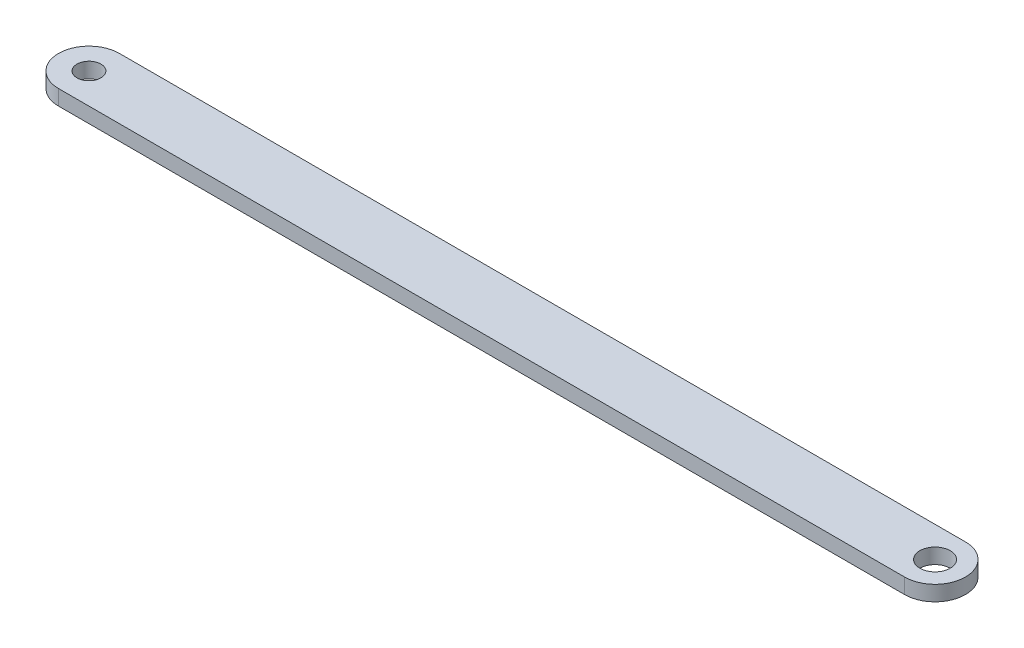
SolidWorks part; units mm, degrees
ref_plane "Front Plane" through (0, 0, 0) normal (0, 0, 1) x (1, 0, 0)
ref_plane "Top Plane" through (0, 0, 0) normal (0, 1, 0) x (1, 0, 0)
ref_plane "Right Plane" through (0, 0, 0) normal (1, 0, 0) x (0, 0, -1)
sketch "Sketch1" plane through (0, 0, 0) normal (0, 1, 0) x (1, 0, 0)
  line L0 (0, 0) -> (176.5478, 0) construction
  line L1 (0, 6.35) -> (176.5478, 6.35)
  line L2 (0, -6.35) -> (176.5478, -6.35)
  arc A0 (0, 6.35) -> (0, -6.35) centre (0, 0) ccw
  arc A1 (176.5478, -6.35) -> (176.5478, 6.35) centre (176.5478, 0) ccw
  circle A2 centre (0, 0) radius 2.5
  circle A3 centre (176.5478, 0) radius 3.175
  point P3 (88.2739, 0)
  dimension "D2" = 5
  dimension "D3" = 6.35
  dimension "D4" = 6.35
  dimension "D1" = 176.5478
extrude "Boss-Extrude1" add sketch "Sketch1" along normal blind 3.175
